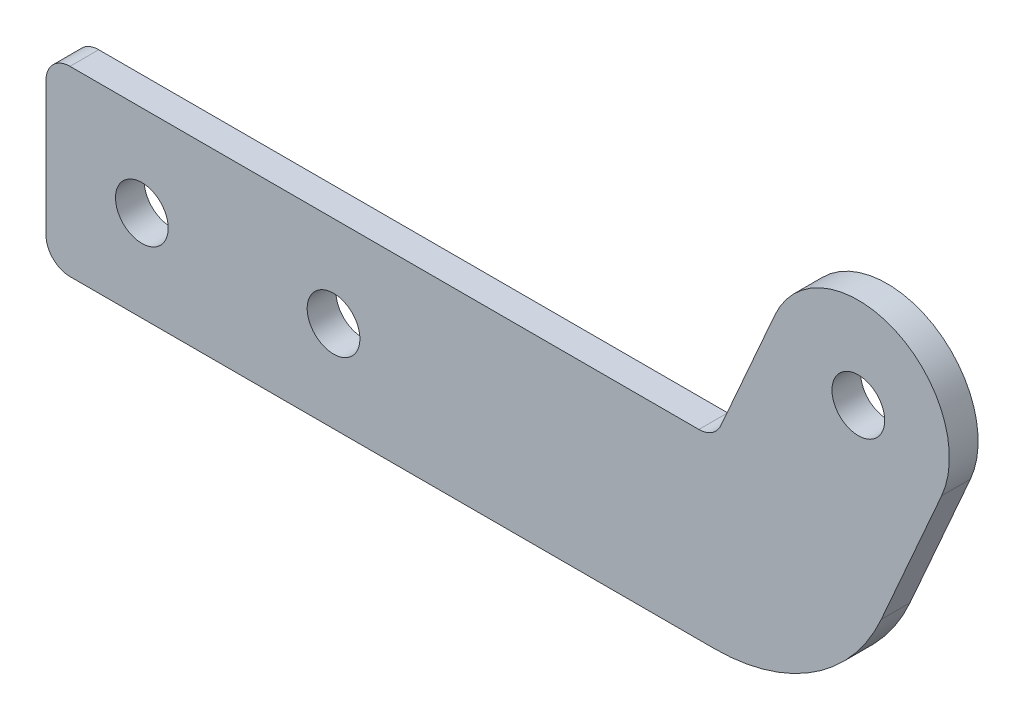
SolidWorks part; units mm, degrees
ref_plane "Front Plane" through (0, 0, 0) normal (0, 0, 1) x (1, 0, 0)
ref_plane "Top Plane" through (0, 0, 0) normal (0, 1, 0) x (1, 0, 0)
ref_plane "Right Plane" through (0, 0, 0) normal (1, 0, 0) x (0, 0, -1)
sketch "Sketch1" plane through (0, 0, 0) normal (0, 0, 1) x (1, 0, 0)
  line L0 (-84.75, -20) -> (-12.5862, -20) construction
  line L1 (8.6953, -3.8266) -> (2.3905, -18.1531)
  line L2 (-84.75, -10.5) -> (-84.75, -29.5)
  line L3 (-84.75, -10.5) -> (-15, -10.5)
  line L5 (-15, -29.5) -> (-515, -29.5) construction
  line L6 (-15, -29.5) -> (-84.75, -29.5)
  line L7 (-15, 9.5) -> (-515, 9.5) construction
  line L8 (-15, -15.42) -> (-15, -4.58) construction
  line L9 (-15, -10.5) -> (-8.6953, 3.8266)
  arc A0 (8.6953, -3.8266) -> (-8.6953, 3.8266) centre (0, 0) ccw
  arc A1 (2.3905, -18.1531) -> (-15, -29.5) centre (-15, -10.5) cw
  dimension "D1" = 69.75
  dimension "D2" = 19
extrude "Boss-Extrude1" add sketch "Sketch1" along normal blind 3
hole_wizard "M5 Clearance Hole1" positions "Sketch5" profile "Sketch4" hole size "M5" standard "ISO" end condition up to next
sketch "Sketch5" plane through (0, 0, 3) normal (0, 0, 1) x (1, 0, 0)
  line L0 (-84.75, -10.5) -> (-84.75, -29.5) construction
  point P0 (-74.75, -20)
  dimension "D1" = 10
sketch "Sketch4" plane through (-74.75, -20, 3) normal (1, 0, 0) x (0, -1, 0)
  line L0 (0, 0) -> (0, 3)
  line L1 (0, 3) -> (2.75, 3)
  line L2 (2.75, 3) -> (2.75, 0)
  line L5 (2.75, 0) -> (0, 0)
  line L11 (0, -6.35) -> (0, 107.95) construction
  dimension "Thru Hole Dia." = 5.5
  dimension "Thru Hole Depth" = 3
hole_wizard "M5 Clearance Hole2" positions "Sketch7" profile "Sketch6" hole size "M5" standard "ISO" end condition up to next
sketch "Sketch7" plane through (0, 0, 3) normal (0, 0, 1) x (1, 0, 0)
  point P0 (-54.75, -20)
  dimension "D1" = 20
sketch "Sketch6" plane through (-54.75, -20, 3) normal (1, 0, 0) x (0, -1, 0)
  line L0 (0, 0) -> (0, 3)
  line L1 (0, 3) -> (2.75, 3)
  line L2 (2.75, 3) -> (2.75, 0)
  line L5 (2.75, 0) -> (0, 0)
  line L11 (0, -6.35) -> (0, 107.95) construction
  dimension "Thru Hole Dia." = 5.5
  dimension "Thru Hole Depth" = 3
hole_wizard "M5 Clearance Hole3" positions "Sketch9" profile "Sketch8" hole size "M5" standard "ISO" end condition up to next
sketch "Sketch9" plane through (0, 0, 3) normal (0, 0, 1) x (1, 0, 0)
  point P0 (0, 0)
sketch "Sketch8" plane through (0, 0, 3) normal (1, 0, 0) x (0, -1, 0)
  line L0 (0, 0) -> (0, 3)
  line L1 (0, 3) -> (2.75, 3)
  line L2 (2.75, 3) -> (2.75, 0)
  line L5 (2.75, 0) -> (0, 0)
  line L11 (0, -6.35) -> (0, 107.95) construction
  dimension "Thru Hole Dia." = 5.5
  dimension "Thru Hole Depth" = 3
fillet "Fillet2" radius 2.5 3 edges at (-84.75, -29.5, 1.5) (-84.75, -10.5, 1.5) (-15, -10.5, 1.5)
